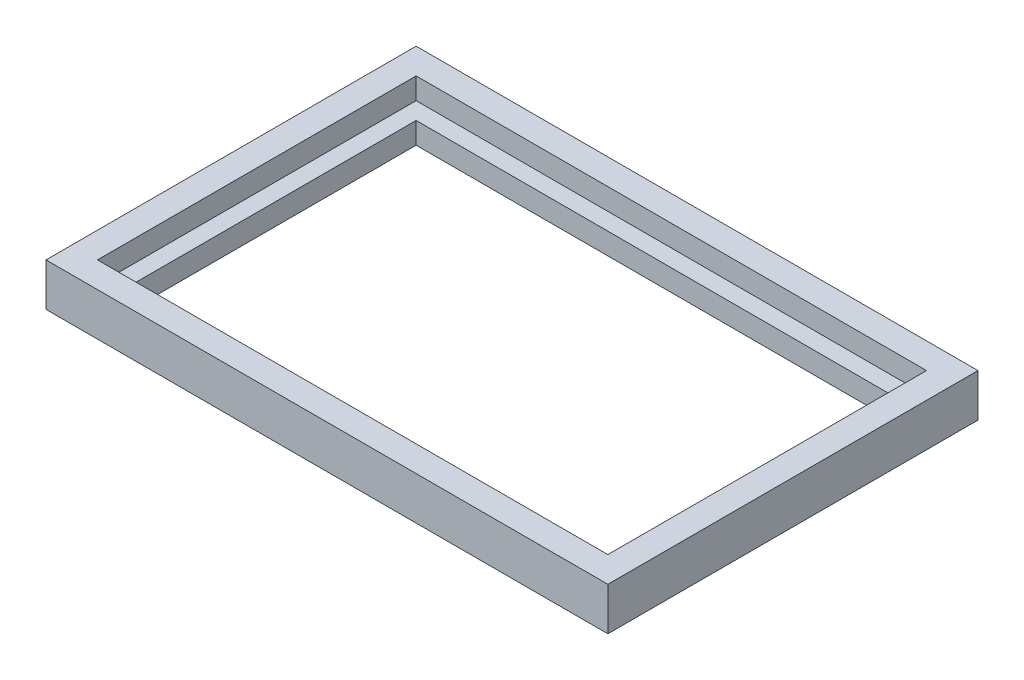
SolidWorks part; units mm, degrees
ref_plane "Front Plane" through (0, 0, 0) normal (0, 0, 1) x (1, 0, 0)
ref_plane "Top Plane" through (0, 0, 0) normal (0, 1, 0) x (1, 0, 0)
ref_plane "Right Plane" through (0, 0, 0) normal (1, 0, 0) x (0, 0, -1)
sketch "Sketch1" plane through (0, 0, 0) normal (0, 1, 0) x (1, 0, 0)
  line L1 (40, -52.5) -> (-40, -52.5)
  line L2 (80, -12.5) -> (80, 12.5)
  line L3 (40, 52.5) -> (-40, 52.5)
  line L4 (-80, -12.5) -> (-80, 12.5)
  arc A1 (-80, -12.5) -> (-40, -52.5) centre (-40, -12.5) ccw
  arc A4 (-40, 52.5) -> (-80, 12.5) centre (-40, 12.5) ccw
  arc A6 (40, -52.5) -> (80, -12.5) centre (40, -12.5) ccw
  arc A7 (80, 12.5) -> (40, 52.5) centre (40, 12.5) ccw
  point P0 (0, 0)
  dimension "D8" = 80
  dimension "D3" = 40
  dimension "D4" = 40
  dimension "D6" = 40
  dimension "D7" = 40
  dimension "D9" = 40
  dimension "D10" = 40
  dimension "D12" = 40
  dimension "D13" = 40
extrude "Boss-Extrude1" add sketch "Sketch1" along normal blind 5
sketch "Sketch6" plane through (0, 5, 0) normal (0, 1, 0) x (1, 0, 0)
  line L0 (0, -52.5) -> (0, 54.1231) construction
  line L1 (-40, -52.5) -> (40, -52.5) construction
sketch "Sketch2" plane through (0, 0, 0) normal (0, -1, 0) x (-1, 0, 0)
  line L0 (17.7907, -43.1354) -> (-30.7093, -43.1354) construction
  line L1 (21.2907, -45.1354) -> (-34.2093, -45.1354)
  line L2 (21.2907, -45.1354) -> (21.2907, -11.9854)
  line L3 (21.2907, -11.9854) -> (-34.2093, -11.9854)
  line L4 (-34.2093, -45.1354) -> (-34.2093, -11.9854)
  line L5 (19.2907, -16.4854) -> (19.2907, -41.6354) construction
  line L6 (-32.2093, -41.6354) -> (-32.2093, -33.8104) construction
  line L7 (-30.7093, -14.9854) -> (17.7907, -14.9854) construction
  dimension "D1" = 2
  dimension "D2" = 2
  dimension "D3" = 2
  dimension "D4" = 3
extrude "Cut-Extrude1" cut sketch "Sketch2" against normal blind 10
sketch "Sketch3" plane through (0, 5, 0) normal (0, 1, 0) x (1, 0, 0)
  line L0 (34.2093, -11.9854) -> (-21.2907, -11.9854) construction
  line L1 (-23.2907, -9.9854) -> (36.2093, -9.9854)
  line L2 (-23.2907, -9.9854) -> (-23.2907, -47.1354)
  line L3 (-23.2907, -47.1354) -> (36.2093, -47.1354)
  line L4 (36.2093, -9.9854) -> (36.2093, -47.1354)
  line L5 (-21.2907, -11.9854) -> (-21.2907, -45.1354) construction
  line L6 (-21.2907, -45.1354) -> (34.2093, -45.1354) construction
  line L7 (34.2093, -45.1354) -> (34.2093, -11.9854) construction
  dimension "D1" = 2
  dimension "D2" = 2
  dimension "D3" = 2
  dimension "D4" = 2
extrude "Cut-Extrude2" cut sketch "Sketch3" against normal blind 2.5
sketch "Sketch4" plane through (0, 5, 0) normal (0, 1, 0) x (1, 0, 0)
  line L5 (43.0299, -32.5) -> (69.4299, -32.5) construction
  line L6 (69.4299, -32.5) -> (69.4299, 1.8) construction
  line L7 (0, 54.1231) -> (0, -52.5) construction
  circle A1 centre (56.2299, -16.5) radius 13.5
  circle A2 centre (-56.2299, -16.5) radius 13.5
  dimension "D6" = 27
  dimension "D4" = 16
  dimension "D5" = 13.2
extrude "Cut-Extrude3" cut sketch "Sketch4" against normal blind 2.5
sketch "Sketch5" plane through (0, 5, 0) normal (0, 1, 0) x (1, 0, 0)
  line L0 (48.5793, 45.5) -> (48.5793, 3) construction
  line L1 (69.4299, -32.5) -> (69.4299, 1.8) construction
  line L2 (43.0299, 1.8) -> (43.0299, -32.5) construction
  line L3 (43.0299, -32.5) -> (69.4299, -32.5) construction
  line L4 (0, 54.1231) -> (0, -52.5) construction
  line L5 (-40, -52.5) -> (40, -52.5) construction
  line L6 (0.0793, 47.5) -> (46.5793, 47.5) construction
  line L7 (48.5793, 3) -> (0.0793, 3) construction
  line L8 (-48.4207, 3) -> (-48.4207, 45.5) construction
  line L9 (-31.7707, 3) -> (38.4293, 3) construction
  line L11 (-31.7707, -47.2) -> (-31.7707, 3) construction
  line L12 (38.4293, -47.2) -> (-31.7707, -47.2) construction
  line L13 (38.4293, 3) -> (38.4293, -47.2) construction
  circle A0 centre (66.0549, -29.425) radius 1.35
  circle A1 centre (46.4049, -29.425) radius 1.35
  circle A2 centre (66.0549, -3.575) radius 1.35
  circle A4 centre (46.4049, -3.575) radius 1.35
  circle A5 centre (-46.4049, -29.425) radius 1.35
  circle A6 centre (-66.0549, -29.425) radius 1.35
  circle A7 centre (-66.0549, -3.575) radius 1.35
  circle A8 centre (-46.4049, -3.575) radius 1.35
  circle A11 centre (46.5793, 44.5) radius 0.95
  circle A12 centre (46.5793, 5) radius 0.95
  circle A13 centre (-46.4207, 5) radius 0.95
  circle A14 centre (-46.4207, 44.5) radius 0.95
  circle A15 centre (-29.5207, 0.75) radius 1.2
  circle A16 centre (-29.5207, -44.95) radius 1.2
  circle A17 centre (36.1793, 0.75) radius 1.2
  dimension "D1" = 2.7
  dimension "D5" = 2.7
  dimension "D6" = 2.7
  dimension "D7" = 2.7
  dimension "D8" = 1.9
  dimension "D13" = 1.9
  dimension "D15" = 1.9
  dimension "D17" = 1.9
  dimension "D20" = 2.4
  dimension "D22" = 2.4
  dimension "D23" = 2.4
  dimension "D2" = 3.375
  dimension "D3" = 3.375
  dimension "D4" = 3.075
  dimension "D9" = 2
  dimension "D10" = 3
  dimension "D11" = 2
  dimension "D12" = 2
  dimension "D14" = 2
  dimension "D16" = 2
  dimension "D18" = 2.25
  dimension "D19" = 2.25
  dimension "D21" = 2.25
  dimension "D24" = 2.25
sketch "Sketch8" plane through (0, 5, 0) normal (0, 1, 0) x (1, 0, 0)
  line L0 (48.5793, 45.5) -> (48.5793, 3) construction
  line L1 (44.5793, 7) -> (-44.4207, 7)
  line L2 (44.5793, 7) -> (44.5793, 43.5)
  line L3 (44.5793, 43.5) -> (-44.4207, 43.5)
  line L4 (-44.4207, 7) -> (-44.4207, 43.5)
  line L5 (48.5793, 3) -> (0.0793, 3) construction
  line L6 (0.0793, 47.5) -> (46.5793, 47.5) construction
  line L7 (-48.4207, 3) -> (-48.4207, 45.5) construction
  dimension "D1" = 4
  dimension "D2" = 4
  dimension "D3" = 4
  dimension "D4" = 4
extrude "Cut-Extrude4" cut sketch "Sketch8" against normal blind 2.5
sketch "Sketch9" plane through (0, 0, 52.5) normal (0, 0, 1) x (1, 0, 0)
  line L0 (-40, 0) -> (40, 0) construction
  line L1 (-80, 0) -> (-40, 0) construction
  line L2 (0, 0) -> (0, 26.0954) construction
  line L3 (-80, 0) -> (-40, 0)
  line L4 (40, 0) -> (80, 0)
  spline S0 degree 3 poles (-80, 0) (-79.948, -3.6737) (-77.5841, -11.3965) (-57.1102, -20.5098) (-48.9028, -1.3509) (-40, 0) knots 0 0 0 0 0.18446 0.474643 1 1 1 1
  spline S1 degree 3 poles (80, 0) (79.948, -3.6737) (77.5841, -11.3965) (57.1102, -20.5098) (48.9028, -1.3509) (40, 0) knots 0 0 0 0 0.18446 0.474643 1 1 1 1
  dimension "D1" = 40
  dimension "D2" = 17
  dimension "D3" = 3
  dimension "D4" = 15
  dimension "D5" = 7
  dimension "D6" = 29
extrude "Boss-Extrude4" add sketch "Sketch9" against normal blind 105
sketch "Sketch10" plane through (0, 5, 0) normal (0, 1, 0) x (1, 0, 0)
  line L0 (-80, 12.5) -> (-80, -12.5)
  line L1 (-40, 52.5) -> (40, 52.5)
  line L2 (80, 12.5) -> (80, -12.5)
  line L3 (-40, -52.5) -> (40, -52.5)
  arc A0 (-80, -12.5) -> (-40, -52.5) centre (-40, -12.5) ccw
  arc A1 (-80, 12.5) -> (-40, 52.5) centre (-40, 12.5) cw
  arc A2 (40, 52.5) -> (80, 12.5) centre (40, 12.5) cw
  arc A3 (80, -12.5) -> (40, -52.5) centre (40, -12.5) cw
extrude "Cut-Extrude5" cut sketch "Sketch10" against normal blind 105 flip side to cut
extrude "Cut-Extrude6" cut sketch "Sketch5" against normal blind 3
sketch "Sketch11" plane through (0, 5, 0) normal (0, 1, 0) x (1, 0, 0)
  line L0 (-21.2907, -45.1354) -> (-21.2907, -11.9854) construction
  line L1 (-26.2907, -6.9854) -> (39.2093, -6.9854)
  line L2 (-26.2907, -6.9854) -> (-26.2907, -50.1354)
  line L3 (-26.2907, -50.1354) -> (39.2093, -50.1354)
  line L4 (39.2093, -6.9854) -> (39.2093, -50.1354)
  line L5 (-21.2907, -11.9854) -> (34.2093, -11.9854) construction
  line L6 (34.2093, -11.9854) -> (34.2093, -45.1354) construction
  line L7 (34.2093, -45.1354) -> (-21.2907, -45.1354) construction
  dimension "D1" = 5
  dimension "D2" = 5
  dimension "D3" = 5
  dimension "D4" = 5
extrude "Cut-Extrude7" cut sketch "Sketch11" against normal blind 10 flip side to cut
